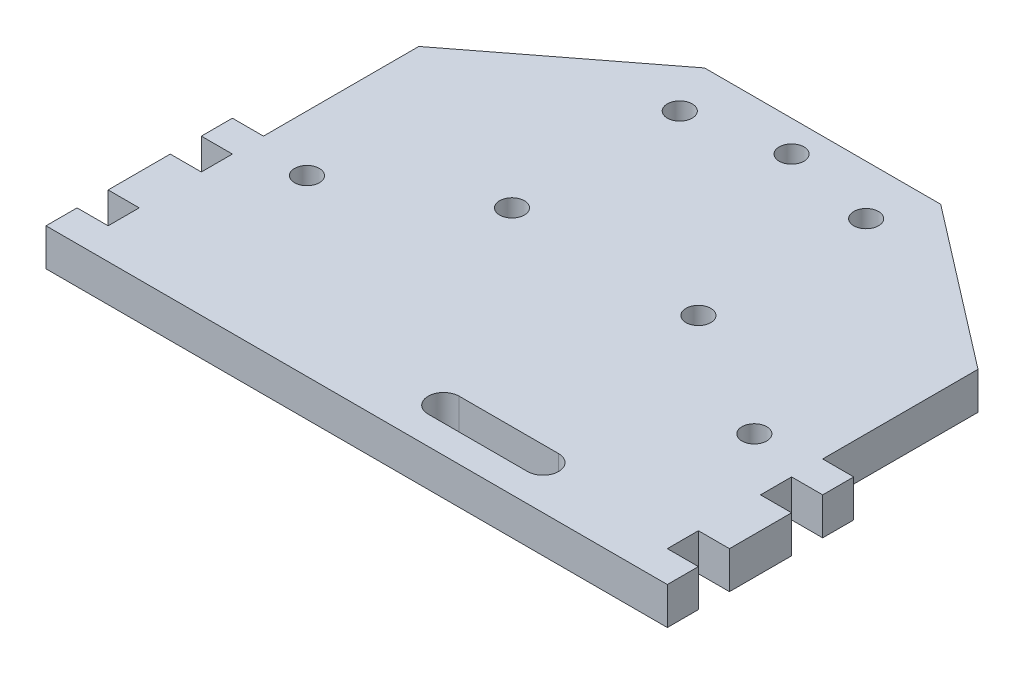
SolidWorks part; units mm, degrees
ref_plane "Front Plane" through (0, 0, 0) normal (0, 0, 1) x (1, 0, 0)
ref_plane "Top Plane" through (0, 0, 0) normal (0, 1, 0) x (1, 0, 0)
ref_plane "Right Plane" through (0, 0, 0) normal (1, 0, 0) x (0, 0, -1)
sketch "Sketch1" plane through (0, 0, 0) normal (0, 1, 0) x (1, 0, 0)
  line L0 (72.9688, 0) -> (-68.392, 0) construction
  line L1 (0, 54.3862) -> (0, -48.3135) construction
  line L2 (-45, 15) -> (-45, -10)
  line L3 (-50, -35) -> (-50, -40)
  line L4 (45, -20) -> (45, -15)
  line L5 (19, 35) -> (-19, 35)
  line L6 (-45, -40) -> (45, -40)
  line L7 (-19, 10.2379) -> (-19, 43.7621) construction
  line L8 (19, 27) -> (19, 35) construction
  line L9 (-19, 35) -> (-45, 15)
  line L10 (19, 35) -> (45, 15)
  line L11 (45, -33) -> (45, -30)
  line L12 (-15, -2) -> (-15, 2) construction
  line L13 (-15, 29) -> (-15, 35) construction
  line L14 (15, 11.9309) -> (15, -51.3384) construction
  line L15 (-10.914, -33) -> (50.3405, -33) construction
  line L16 (7, -33) -> (23, -33) construction
  line L17 (7, -30.5) -> (23, -30.5)
  line L18 (7, -35.5) -> (23, -35.5)
  line L19 (45, -35) -> (45, -33)
  line L20 (45, -10) -> (45, 15)
  line L21 (-50, -40) -> (-45, -40)
  line L22 (-50, -35) -> (-45, -35)
  line L23 (-45, -35) -> (-45, -30)
  line L24 (-50, -30) -> (-50, -20)
  line L25 (-45, -30) -> (-50, -30)
  line L26 (-45, -20) -> (-45, -15)
  line L27 (-50, -20) -> (-45, -20)
  line L28 (-50, -15) -> (-50, -10)
  line L29 (-45, -15) -> (-50, -15)
  line L30 (-50, -10) -> (-45, -10)
  line L31 (50, -40) -> (45, -40)
  line L32 (50, -35) -> (50, -40)
  line L33 (50, -35) -> (45, -35)
  line L34 (45, -30) -> (50, -30)
  line L35 (50, -30) -> (50, -20)
  line L36 (50, -20) -> (45, -20)
  line L37 (45, -15) -> (50, -15)
  line L38 (50, -15) -> (50, -10)
  line L39 (50, -10) -> (45, -10)
  circle A0 centre (15, 0) radius 2
  circle A1 centre (-15, 0) radius 2
  arc A2 (7, -30.5) -> (7, -35.5) centre (7, -33) ccw
  arc A3 (23, -35.5) -> (23, -30.5) centre (23, -33) ccw
  circle A4 centre (15, 27) radius 2
  circle A5 centre (-15, 27) radius 2
  circle A6 centre (0, 30) radius 2
  circle A8 centre (-36, -12) radius 2
  circle A9 centre (36, -12) radius 2
  point P27 (-19, 27)
  point P36 (15, -33)
  point P59 (-47.5, -20)
  point P62 (-47.5, -15)
  dimension "D5" = 15
  dimension "D6" = 15
  dimension "D7" = 8
  dimension "D8" = 8
  dimension "D9" = 15
  dimension "D11" = 16
  dimension "D13" = 5
  dimension "D16" = 12
  dimension "D1" = 35
  dimension "D2" = 33
  dimension "D4" = 45
  dimension "D10" = 15
  dimension "D12" = 8
  dimension "D14" = 12
  dimension "D17" = 5
  dimension "D18" = 40
  dimension "D19" = 5
  dimension "D20" = 5
  dimension "D21" = 10
  dimension "D22" = 5
  dimension "D23" = 5
extrude "Boss-Extrude1" add sketch "Sketch1" along normal blind 6
